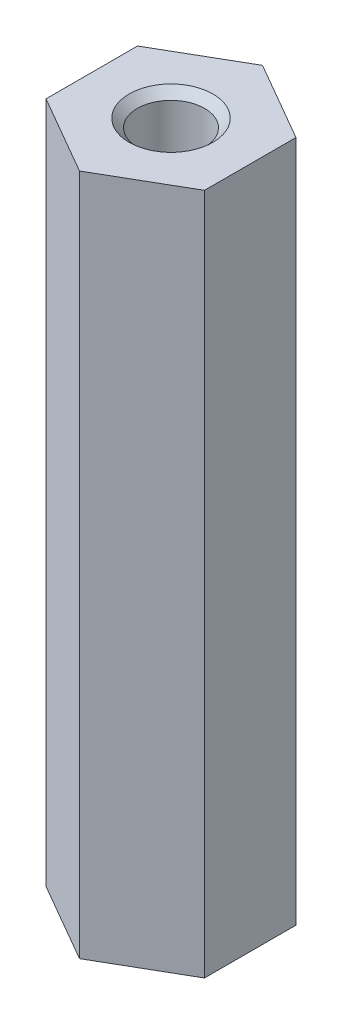
SolidWorks part; units mm, degrees
ref_plane "Front Plane" through (0, 0, 0) normal (0, 0, 1) x (1, 0, 0)
ref_plane "Top Plane" through (0, 0, 0) normal (0, 1, 0) x (1, 0, 0)
ref_plane "Right Plane" through (0, 0, 0) normal (1, 0, 0) x (0, 0, -1)
sketch "Sketch1" plane through (0, 0, 0) normal (0, 1, 0) x (1, 0, 0)
  line L1 (0, -5.4993) -> (4.7625, -2.7496)
  line L2 (4.7625, -2.7496) -> (4.7625, 2.7496)
  line L3 (4.7625, 2.7496) -> (0, 5.4993)
  line L4 (0, 5.4993) -> (-4.7625, 2.7496)
  line L5 (-4.7625, 2.7496) -> (-4.7625, -2.7496)
  line L6 (-4.7625, -2.7496) -> (0, -5.4993)
  circle A0 centre (0, 0) radius 4.7625 construction
  dimension "D1" = 9.525
extrude "Boss-Extrude1" add sketch "Sketch1" along normal blind 41
hole_wizard "#10-32 Tapped Hole1" positions "Sketch2" profile "Sketch4" tap size "#10-32" standard "ANSI Inch"
sketch "Sketch2" plane through (0, 41, 0) normal (0, 1, 0) x (1, 0, 0)
  point P0 (0, 0)
sketch "Sketch4" plane through (0, 41, 0) normal (1, 0, 0) x (0, 0, 1)
  line L0 (0, 0) -> (0, 9.2133)
  line L1 (0, 9.2133) -> (2.0193, 8)
  line L2 (2.0193, 8) -> (2.0193, 0)
  line L5 (2.0193, 0) -> (0, 0)
  line L10 (0, 9.2133) -> (-2.0193, 8) construction
  line L11 (0, -6.35) -> (0, 107.95) construction
  dimension "Tap Drill Dia." = 4.0386
  dimension "Tap Drill Depth" = 8
  dimension "Drill Angle" = 118
cosmetic thread "Hole Thread1" parameters "D1"=7, "D2"=4.826
hole_wizard "#10-32 Tapped Hole2" positions "Sketch5" profile "Sketch6" tap size "#10-32" standard "ANSI Inch"
sketch "Sketch5" plane through (0, 0, 0) normal (0, -1, 0) x (-1, 0, 0)
  point P0 (0, 0)
sketch "Sketch6" plane through (0, 0, 0) normal (1, 0, 0) x (0, 0, -1)
  line L0 (0, 0) -> (0, 9.2133)
  line L1 (0, 9.2133) -> (2.0193, 8)
  line L2 (2.0193, 8) -> (2.0193, 0)
  line L5 (2.0193, 0) -> (0, 0)
  line L10 (0, 9.2133) -> (-2.0193, 8) construction
  line L11 (0, -6.35) -> (0, 107.95) construction
  dimension "Tap Drill Dia." = 4.0386
  dimension "Tap Drill Depth" = 8
  dimension "Drill Angle" = 118
cosmetic thread "Hole Thread2"
chamfer "Chamfer1" distance 0.5 2 edges at (0, 0, -2.0193) (0, 41, 2.0193)
